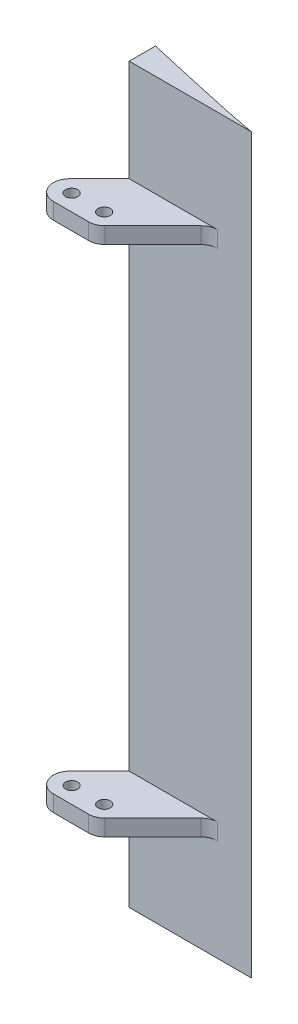
SolidWorks part; units mm, degrees
ref_plane "Front Plane" through (0, 0, 0) normal (0, 0, 1) x (1, 0, 0)
ref_plane "Top Plane" through (0, 0, 0) normal (0, 1, 0) x (1, 0, 0)
ref_plane "Right Plane" through (0, 0, 0) normal (1, 0, 0) x (0, 0, -1)
sketch "Sketch1" plane through (0, 0, 0) normal (0, 1, 0) x (1, 0, 0)
  line L0 (-23.8352, 0) -> (26.1648, 0)
  spline S0 degree 3 poles (-24.2676, 1.2562) (-22.2782, 3.5536) (-18.7384, 4.7933) (-8.8501, 5.7749) (4.1327, 5.525) (19.2119, 1.1626) (26.1648, 0) knots 0.021997 0.021997 0.021997 0.021997 0.155271 0.206186 0.531145 1 1 1 1
  spline S1 degree 2 poles (-24.2676, 1.2562) (-25.3671, 0.1243) (-23.8352, 0) knots 0 0 0 1 1 1
  dimension "D1" = 50
extrude "Boss-Extrude1" add sketch "Sketch1" along normal blind 100
ref_plane "Plane1" through (0, 0, 10) normal (0, 0, 1) x (1, 0, 0)
sketch "Sketch2" plane through (0, 0, 10) normal (0, 0, 1) x (1, 0, 0)
  line L0 (26.1648, 100) -> (26.1648, 0) construction
  line L1 (26.1648, 95) -> (11.1648, 95)
  line L3 (26.1648, 5) -> (11.1648, 5)
  line L4 (11.1648, 95) -> (11.1648, 5)
  line L5 (-23.8352, 100) -> (26.1648, 100) construction
  line L6 (-23.8352, 0) -> (26.1648, 0) construction
  line L7 (26.1648, 95) -> (26.1648, 100)
  line L8 (26.1648, 100) -> (-24.727, 100)
  line L9 (-24.727, 100) -> (-24.727, 0)
  line L10 (-24.727, 0) -> (26.1648, 0)
  line L11 (26.1648, 0) -> (26.1648, 5)
  dimension "D1" = 15
  dimension "D2" = 5
  dimension "D3" = 5
extrude "Cut-Extrude4" cut sketch "Sketch2" against normal blind 100
sketch "Sketch3" plane through (0, 5, 0) normal (0, -1, 0) x (1, 0, 0)
  line L0 (15.6593, 0) -> (14.165, -1.4943)
  line L1 (11.1648, 0) -> (26.1648, 0) construction
  dimension "D1" = 45
sketch "Sketch4" plane through (0, 0, 0) normal (0, 0, 1) x (1, 0, 0)
  line L0 (11.1648, 95) -> (11.1648, 5) construction
  line L1 (11.1648, 82.5) -> (21.1648, 82.5)
  line L2 (11.1648, 82.5) -> (11.1648, 80.5)
  line L3 (11.1648, 80.5) -> (21.1648, 80.5)
  line L4 (21.1648, 82.5) -> (21.1648, 80.5)
  line L5 (26.1648, 95) -> (11.1648, 95) construction
  line L6 (11.1648, 17.5) -> (21.1648, 17.5)
  line L7 (11.1648, 17.5) -> (11.1648, 19.5)
  line L8 (11.1648, 19.5) -> (21.1648, 19.5)
  line L9 (21.1648, 17.5) -> (21.1648, 19.5)
  line L10 (11.1648, 5) -> (26.1648, 5) construction
  dimension "D1" = 10
  dimension "D2" = 2
  dimension "D3" = 12.5
  dimension "D4" = 10
  dimension "D5" = 2
  dimension "D6" = 12.5
sketch "Sketch5" plane through (0, 5, 0) normal (0, -1, 0) x (1, 0, 0)
  line L0 (12.4613, 0) -> (13.7134, -1.2521)
  line L1 (11.1648, 0) -> (26.1648, 0) construction
  dimension "D1" = 45
extrude "Boss-Extrude2" add sketch "Sketch4" along direction (0.7071, 0, -0.7071) on the side of the normal blind 10 contours L1 L4 L3 L2 | L6 L9 L8 L7
fillet "Fillet2" radius 2 6 edges at (21.1648, 18.5, 0) (14.0938, 18.5, 7.0711) (4.0938, 18.5, 7.0711) (21.1648, 81.5, 0) (14.0938, 81.5, 7.0711) (4.0938, 81.5, 7.0711)
sketch "Sketch6" plane through (0, 82.5, 0) normal (0, 1, 0) x (1, 0, 0)
  line L0 (8.9222, -7.0711) -> (13.2653, -7.0711) construction
  circle A0 centre (9.1648, -5.0711) radius 0.75
  circle A1 centre (13.1648, -5.0711) radius 0.75
  dimension "D1" = 2
  dimension "D2" = 2
  dimension "D3" = 1.5
  dimension "D4" = 1.5
  dimension "D5" = 2
  dimension "D6" = 2
extrude "Cut-Extrude5" cut sketch "Sketch6" against normal blind 110
